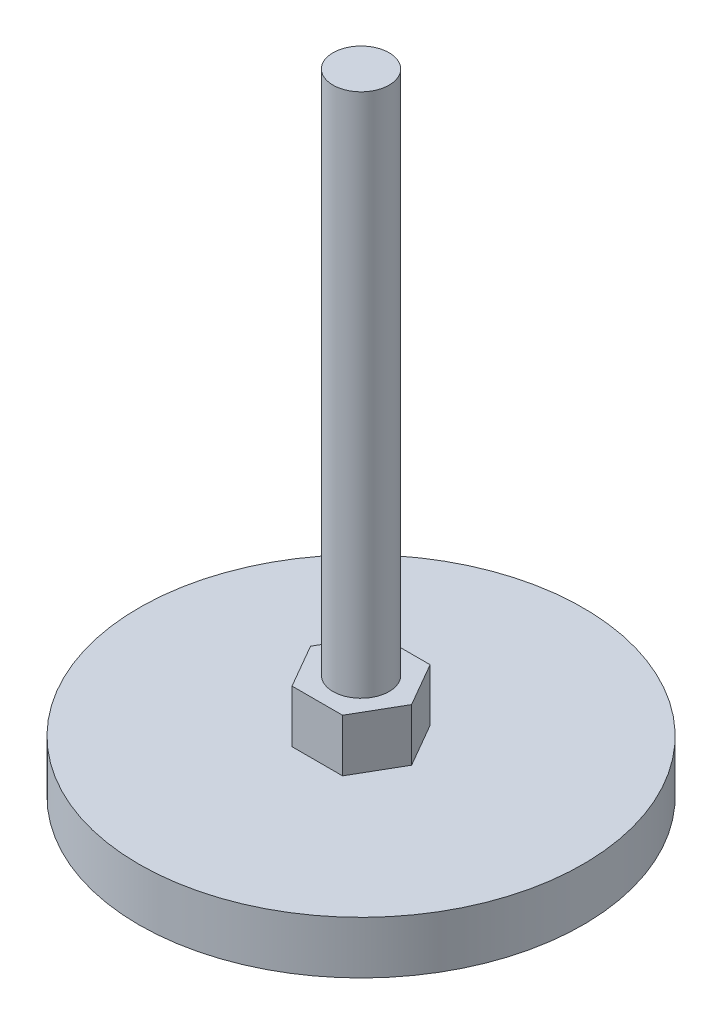
SolidWorks part; units mm, degrees
ref_plane "Alzado" through (0, 0, 0) normal (0, 0, 1) x (1, 0, 0)
ref_plane "Planta" through (0, 0, 0) normal (0, 1, 0) x (1, 0, 0)
ref_plane "Vista lateral" through (0, 0, 0) normal (1, 0, 0) x (0, 0, -1)
sketch "Croquis1" plane through (0, 0, 0) normal (0, 1, 0) x (1, 0, 0)
  circle A0 centre (0, 0) radius 50.7442
extrude "Saliente-Extruir1" add sketch "Croquis1" along normal blind 12
sketch "Croquis2" plane through (0, 12, 0) normal (0, 1, 0) x (1, 0, 0)
  line L1 (11.547, 0) -> (5.7735, 10)
  line L2 (5.7735, 10) -> (-5.7735, 10)
  line L3 (-5.7735, 10) -> (-11.547, 0)
  line L4 (-11.547, 0) -> (-5.7735, -10)
  line L5 (-5.7735, -10) -> (5.7735, -10)
  line L6 (5.7735, -10) -> (11.547, 0)
  circle A0 centre (0, 0) radius 10 construction
extrude "Saliente-Extruir2" add sketch "Croquis2" along normal blind 12
sketch "Croquis3" plane through (0, 24, 0) normal (0, 1, 0) x (1, 0, 0)
  circle A0 centre (0, 0) radius 6.4122
extrude "Saliente-Extruir3" add sketch "Croquis3" along normal blind 120
